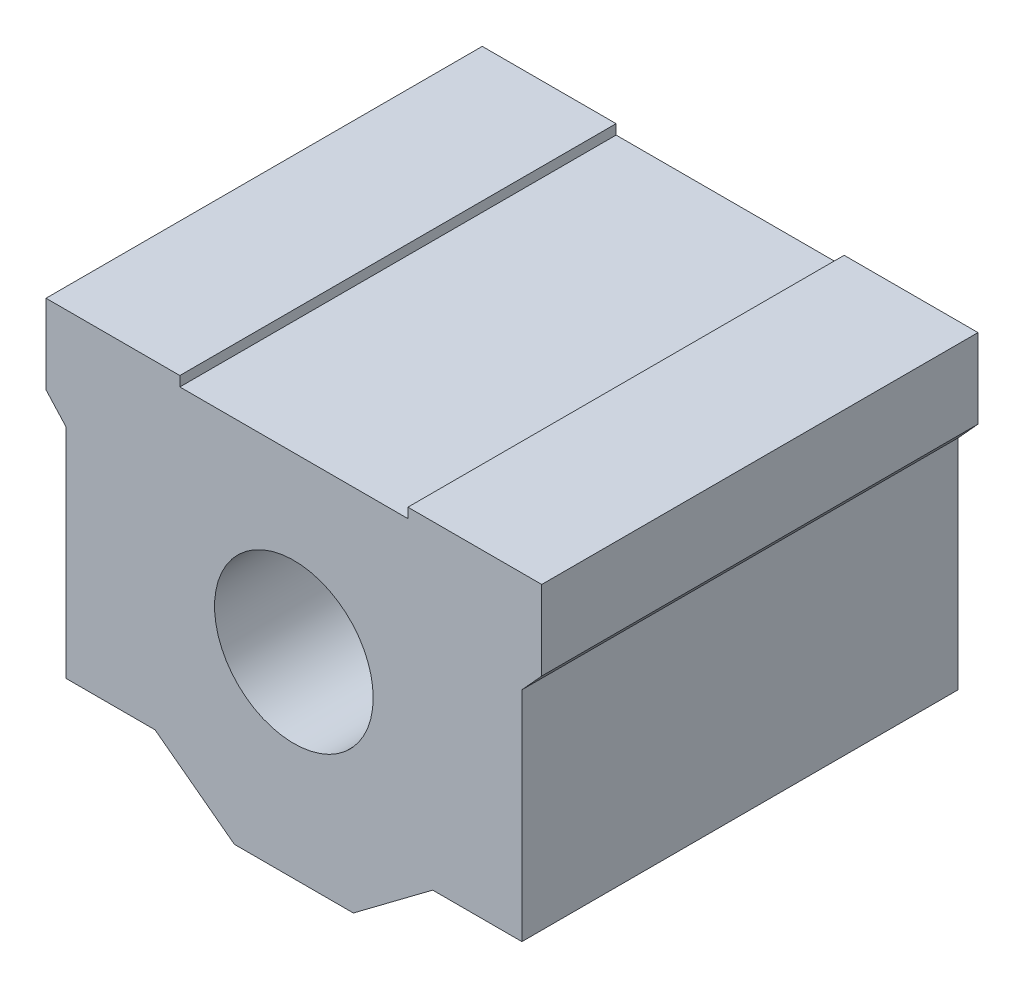
SolidWorks part; units mm, degrees
ref_plane "前视基准面" through (0, 0, 0) normal (0, 0, 1) x (1, 0, 0)
ref_plane "上视基准面" through (0, 0, 0) normal (0, 1, 0) x (1, 0, 0)
ref_plane "右视基准面" through (0, 0, 0) normal (1, 0, 0) x (0, 0, -1)
sketch "草图1" plane through (0, 0, 0) normal (0, 0, 1) x (1, 0, 0)
  line L0 (0, 42.0934) -> (0, 0) construction
  line L1 (0, 0) -> (49.8045, 0) construction
  line L2 (6, 0) -> (-6, 0)
  line L3 (-6, 0) -> (-14, 6)
  line L4 (-14, 6) -> (-23, 6)
  line L5 (-23, 6) -> (-23, 28)
  line L6 (-23, 28) -> (-25, 30.2)
  line L7 (-25, 30.2) -> (-25, 38.2)
  line L8 (-25, 38.2) -> (-11.5, 38.2)
  line L9 (-11.5, 38.2) -> (-11.5, 37.2)
  line L10 (-11.5, 37.2) -> (11.5, 37.2)
  line L11 (14, 6) -> (23, 6)
  line L12 (6, 0) -> (14, 6)
  line L13 (23, 28) -> (25, 30.2)
  line L14 (23, 6) -> (23, 28)
  line L15 (25, 30.2) -> (25, 38.2)
  line L16 (11.5, 38.2) -> (11.5, 37.2)
  line L17 (25, 38.2) -> (11.5, 38.2)
  circle A0 centre (0, 19.8) radius 8
  point P23 (0, 37.2)
  dimension "D1" = 16
  dimension "D2" = 50
  dimension "D3" = 38.2
  dimension "D4" = 19.8
  dimension "D5" = 46
  dimension "D6" = 12
  dimension "D7" = 23
  dimension "D8" = 1
  dimension "D9" = 32.2
  dimension "D10" = 9
  dimension "D11" = 22
  dimension "D12" = 8
extrude "凸台-拉伸1" add sketch "草图1" along normal blind 44
